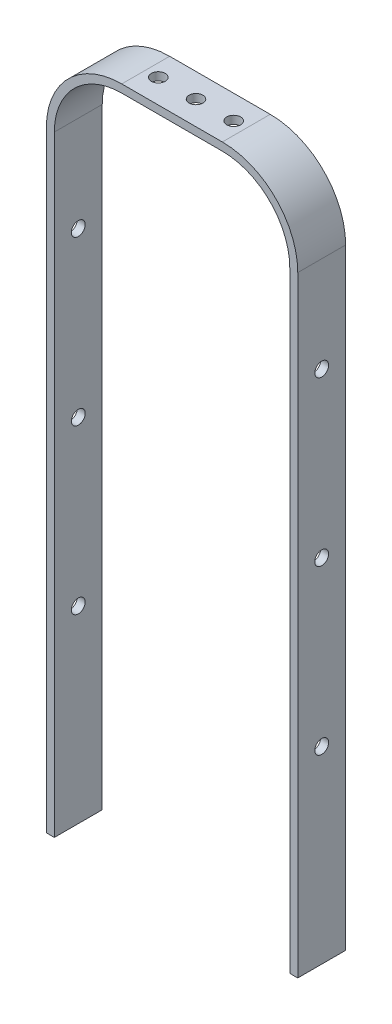
SolidWorks part; units mm, degrees
ref_plane "Front Plane" through (0, 0, 0) normal (0, 0, 1) x (1, 0, 0)
ref_plane "Top Plane" through (0, 0, 0) normal (0, 1, 0) x (1, 0, 0)
ref_plane "Right Plane" through (0, 0, 0) normal (1, 0, 0) x (0, 0, -1)
sketch "Sketch1" plane through (0, 0, 0) normal (0, 0, 1) x (1, 0, 0)
  line L0 (50, 0) -> (50, 243)
  line L1 (0, 0) -> (0, 109.6692) construction
  line L2 (46.825, 243) -> (46.825, 0)
  line L3 (46.825, 0) -> (50, 0)
  line L4 (20, 273) -> (-20, 273)
  line L6 (-20, 269.825) -> (20, 269.825)
  line L7 (-46.825, 0) -> (-50, 0)
  line L8 (-46.825, 243) -> (-46.825, 0)
  line L9 (-50, 0) -> (-50, 243)
  arc A0 (50, 243) -> (20, 273) centre (20, 243) ccw
  arc A1 (20, 269.825) -> (46.825, 243) centre (20, 243) cw
  arc A2 (-20, 269.825) -> (-46.825, 243) centre (-20, 243) ccw
  arc A3 (-50, 243) -> (-20, 273) centre (-20, 243) cw
  dimension "D4" = 26.825
  dimension "D5" = 273
  dimension "D1" = 100
  dimension "D2" = 46.825
extrude "Boss-Extrude1" add sketch "Sketch1" along normal mid plane 19.05
sketch "Sketch12" plane through (0, 273, 0) normal (0, 1, 0) x (1, 0, 0)
  line L0 (-20, -9.525) -> (-20, 9.525) construction
  line L1 (20, -9.525) -> (20, 9.525) construction
  circle A0 centre (0, 0) radius 2.75
  circle A1 centre (-15, 0) radius 2.75
  circle A4 centre (15, 0) radius 2.75
  dimension "D1" = 5.5
  dimension "D2" = 5
  dimension "D3" = 5
extrude "Cut-Extrude2" cut sketch "Sketch12" against normal through all
sketch "Sketch13" plane through (50, 0, 0) normal (1, 0, 0) x (0, 0, -1)
  line L0 (0, 243) -> (0, 0) construction
  line L1 (-9.525, 243) -> (9.525, 243) construction
  line L2 (-9.525, 0) -> (9.525, 0) construction
  circle A0 centre (0, 205) radius 2.75
  circle A1 centre (0, 140) radius 2.75
  circle A2 centre (0, 75) radius 2.75
  dimension "D1" = 5.5
  dimension "D2" = 65
  dimension "D3" = 65
  dimension "D4" = 205
extrude "Cut-Extrude3" cut sketch "Sketch13" against normal through all both and the other way through all
